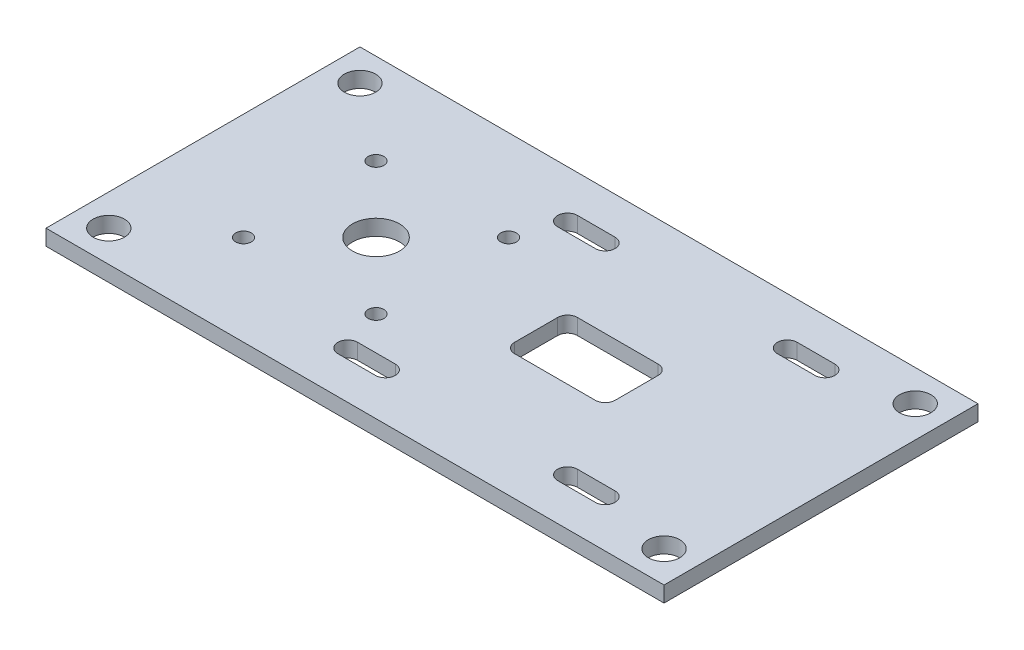
SolidWorks part; units mm, degrees
ref_plane "Front Plane" through (0, 0, 0) normal (0, 0, 1) x (1, 0, 0)
ref_plane "Top Plane" through (0, 0, 0) normal (0, 1, 0) x (1, 0, 0)
ref_plane "Right Plane" through (0, 0, 0) normal (1, 0, 0) x (0, 0, -1)
sketch "Sketch7" plane through (0, 0, 0) normal (0, 1, 0) x (1, 0, 0)
  line L0 (0, 114.3) -> (12.7, 114.3) construction
  line L1 (0, 0) -> (250, 0)
  line L2 (0, 0) -> (0, 127)
  line L3 (0, 127) -> (250, 127)
  line L4 (250, 0) -> (250, 127)
  line L5 (12.7, 114.3) -> (12.7, 127) construction
  line L6 (12.7, 114.3) -> (237.3, 114.3) construction
  line L7 (12.7, 114.3) -> (12.7, 12.7) construction
  line L8 (12.7, 12.7) -> (237.3, 12.7) construction
  line L9 (237.3, 114.3) -> (237.3, 12.7) construction
  line L10 (237.3, 0) -> (237.3, 12.7) construction
  line L11 (237.3, 12.7) -> (250, 12.7) construction
  line L13 (205.25, 8.25) -> (94.75, 8.25) construction
  line L14 (205.25, 8.25) -> (205.25, 118.75) construction
  line L15 (205.25, 118.75) -> (94.75, 118.75) construction
  line L16 (94.75, 8.25) -> (94.75, 118.75) construction
  line L17 (205.25, 8.25) -> (94.75, 118.75) construction
  line L18 (205.25, 118.75) -> (94.75, 8.25) construction
  line L19 (194.45, 19.05) -> (105.55, 19.05) construction
  line L20 (194.45, 19.05) -> (194.45, 107.95) construction
  line L21 (194.45, 107.95) -> (105.55, 107.95) construction
  line L22 (105.55, 19.05) -> (105.55, 107.95) construction
  line L23 (194.45, 19.05) -> (105.55, 107.95) construction
  line L24 (194.45, 107.95) -> (105.55, 19.05) construction
  line L25 (96.8064, 36.6936) -> (43.1936, 36.6936) construction
  line L26 (96.8064, 36.6936) -> (96.8064, 90.3064) construction
  line L27 (96.8064, 90.3064) -> (43.1936, 90.3064) construction
  line L28 (43.1936, 36.6936) -> (43.1936, 90.3064) construction
  line L29 (96.8064, 36.6936) -> (43.1936, 90.3064) construction
  line L30 (96.8064, 90.3064) -> (43.1936, 36.6936) construction
  line L31 (248.2985, 12.7) -> (242.7993, 22.225) construction
  line L32 (242.7993, 22.225) -> (231.8007, 22.225) construction
  line L33 (231.8007, 22.225) -> (226.3015, 12.7) construction
  line L34 (226.3015, 12.7) -> (231.8007, 3.175) construction
  line L35 (231.8007, 3.175) -> (242.7993, 3.175) construction
  line L36 (242.7993, 3.175) -> (248.2985, 12.7) construction
  line L37 (198.2028, 25.55) -> (190.6972, 25.55) construction
  line L38 (190.6972, 25.55) -> (186.9444, 19.05) construction
  line L39 (186.9444, 19.05) -> (190.6972, 12.55) construction
  line L40 (190.6972, 12.55) -> (198.2028, 12.55) construction
  line L41 (198.2028, 12.55) -> (201.9556, 19.05) construction
  line L42 (201.9556, 19.05) -> (198.2028, 25.55) construction
  circle A0 centre (12.7, 114.3) radius 6.35
  circle A1 centre (237.3, 114.3) radius 6.35
  circle A2 centre (237.3, 12.7) radius 6.35 construction
  circle A3 centre (12.7, 12.7) radius 6.35
  circle A4 centre (105.55, 107.95) radius 4
  circle A5 centre (194.45, 107.95) radius 4
  circle A6 centre (194.45, 19.05) radius 4
  circle A7 centre (105.55, 19.05) radius 4
  circle A8 centre (150, 63.5) radius 12.5
  circle A9 centre (43.1936, 90.3064) radius 3.175
  circle A10 centre (96.8064, 90.3064) radius 3.175
  circle A11 centre (96.8064, 36.6936) radius 3.175
  circle A12 centre (43.1936, 36.6936) radius 3.175
  circle A13 centre (70, 63.5) radius 9.525
  circle A14 centre (237.3, 12.7) radius 9.525 construction
  circle A15 centre (194.45, 19.05) radius 6.5 construction
  circle A16 centre (70, 63.5) radius 56 construction
  circle A17 centre (150, 63.5) radius 24 construction
  point P17 (150, 63.5)
  point P24 (250, 63.5)
  point P26 (150, 63.5)
  point P31 (70, 63.5)
  dimension "D1" = 12.7
  dimension "D6" = 8
  dimension "D7" = 25
  dimension "D9" = 6.35
  dimension "D10" = 19.05
  dimension "D16" = 112
  dimension "D17" = 48
  dimension "D2" = 110.5
  dimension "D3" = 127
  dimension "D4" = 250
  dimension "D5" = 88.9
  dimension "D8" = 12.7
  dimension "D11" = 80
  dimension "D12" = 19.05
  dimension "D13" = 13
  dimension "D14" = 70
  dimension "D15" = 37.91
sketch "Sketch1" plane through (0, 0, 0) normal (0, 1, 0) x (1, 0, 0)
  line L0 (0, 0) -> (250, 0) construction
  line L1 (250, 0) -> (250, 127) construction
  line L2 (0, 127) -> (250, 127) construction
  line L3 (0, 0) -> (0, 127) construction
  line L4 (0, 0) -> (250, 0)
  line L5 (250, 0) -> (250, 127)
  line L6 (0, 127) -> (250, 127)
  line L7 (0, 0) -> (0, 127)
extrude "Boss-Extrude1" add sketch "Sketch1" along normal blind 6.35
sketch "Sketch2" plane through (0, 6.35, 0) normal (0, 1, 0) x (1, 0, 0)
  circle A0 centre (237.3, 12.7) radius 6.35 construction
  circle A1 centre (237.3, 114.3) radius 6.35 construction
  circle A2 centre (12.7, 12.7) radius 6.35 construction
  circle A3 centre (12.7, 114.3) radius 6.35 construction
  circle A4 centre (237.3, 12.7) radius 6.35
  circle A5 centre (237.3, 114.3) radius 6.35
  circle A6 centre (12.7, 12.7) radius 6.35
  circle A7 centre (12.7, 114.3) radius 6.35
  circle A8 centre (43.1936, 36.6936) radius 3.175 construction
  circle A9 centre (96.8064, 36.6936) radius 3.175 construction
  circle A10 centre (96.8064, 90.3064) radius 3.175 construction
  circle A11 centre (43.1936, 90.3064) radius 3.175 construction
  circle A12 centre (70, 63.5) radius 9.525 construction
  circle A13 centre (105.55, 19.05) radius 4 construction
  circle A14 centre (194.45, 19.05) radius 4 construction
  circle A15 centre (194.45, 107.95) radius 4 construction
  circle A16 centre (105.55, 107.95) radius 4 construction
  circle A17 centre (150, 63.5) radius 12.5 construction
  circle A18 centre (43.1936, 36.6936) radius 3.175
  circle A19 centre (96.8064, 36.6936) radius 3.175
  circle A20 centre (96.8064, 90.3064) radius 3.175
  circle A21 centre (43.1936, 90.3064) radius 3.175
  circle A22 centre (70, 63.5) radius 9.525
  circle A23 centre (105.55, 19.05) radius 4
  circle A24 centre (194.45, 19.05) radius 4
  circle A25 centre (194.45, 107.95) radius 4
  circle A26 centre (105.55, 107.95) radius 4
  circle A27 centre (150, 63.5) radius 12.5
extrude "Cut-Extrude1" cut sketch "Sketch2" against normal through all
sketch "Sketch8" plane through (0, 6.35, 0) normal (0, 1, 0) x (1, 0, 0)
  line L0 (103.01, 107.95) -> (118.25, 107.95) construction
  line L1 (103.01, 111.95) -> (118.25, 111.95)
  line L2 (103.01, 103.95) -> (118.25, 103.95)
  line L3 (191.91, 107.95) -> (207.15, 107.95) construction
  line L4 (191.91, 111.95) -> (207.15, 111.95)
  line L5 (191.91, 103.95) -> (207.15, 103.95)
  line L6 (103.01, 19.05) -> (118.25, 19.05) construction
  line L7 (103.01, 23.05) -> (118.25, 23.05)
  line L8 (103.01, 15.05) -> (118.25, 15.05)
  line L9 (191.91, 19.05) -> (207.15, 19.05) construction
  line L10 (191.91, 23.05) -> (207.15, 23.05)
  line L11 (191.91, 15.05) -> (207.15, 15.05)
  arc A0 (103.01, 111.95) -> (103.01, 103.95) centre (103.01, 107.95) ccw
  arc A1 (118.25, 103.95) -> (118.25, 111.95) centre (118.25, 107.95) ccw
  circle A2 centre (105.55, 107.95) radius 4 construction
  arc A3 (191.91, 111.95) -> (191.91, 103.95) centre (191.91, 107.95) ccw
  arc A4 (207.15, 103.95) -> (207.15, 111.95) centre (207.15, 107.95) ccw
  arc A5 (103.01, 23.05) -> (103.01, 15.05) centre (103.01, 19.05) ccw
  arc A6 (118.25, 15.05) -> (118.25, 23.05) centre (118.25, 19.05) ccw
  arc A7 (191.91, 23.05) -> (191.91, 15.05) centre (191.91, 19.05) ccw
  arc A8 (207.15, 15.05) -> (207.15, 23.05) centre (207.15, 19.05) ccw
  circle A9 centre (194.45, 107.95) radius 4 construction
  point P2 (110.63, 107.95)
  point P11 (199.53, 107.95)
  point P16 (110.63, 19.05)
  point P23 (199.53, 19.05)
  point P30 (105.55, 107.95)
  point P33 (105.55, 19.05)
  point P35 (194.45, 19.05)
  dimension "D1" = 2.54
  dimension "D3" = 2.54
  dimension "D2" = 15.24
extrude "Cut-Extrude2" cut sketch "Sketch8" against normal through all
sketch "Sketch9" plane through (0, 6.35, 0) normal (0, 1, 0) x (1, 0, 0)
  line L0 (134.76, 63.5) -> (150, 63.5) construction
  line L1 (134.76, 50.8) -> (175.4, 50.8)
  line L2 (134.76, 50.8) -> (134.76, 76.2)
  line L3 (134.76, 76.2) -> (175.4, 76.2)
  line L4 (175.4, 50.8) -> (175.4, 76.2)
  circle A1 centre (150, 63.5) radius 12.5 construction
  dimension "D1" = 15.24
  dimension "D2" = 25.4
  dimension "D3" = 25.4
extrude "Cut-Extrude3" cut sketch "Sketch9" against normal through all
fillet "Fillet1" radius 3.9688 4 edges at (134.76, 3.175, -50.8) (175.4, 3.175, -50.8) (175.4, 3.175, -76.2) (134.76, 3.175, -76.2)
